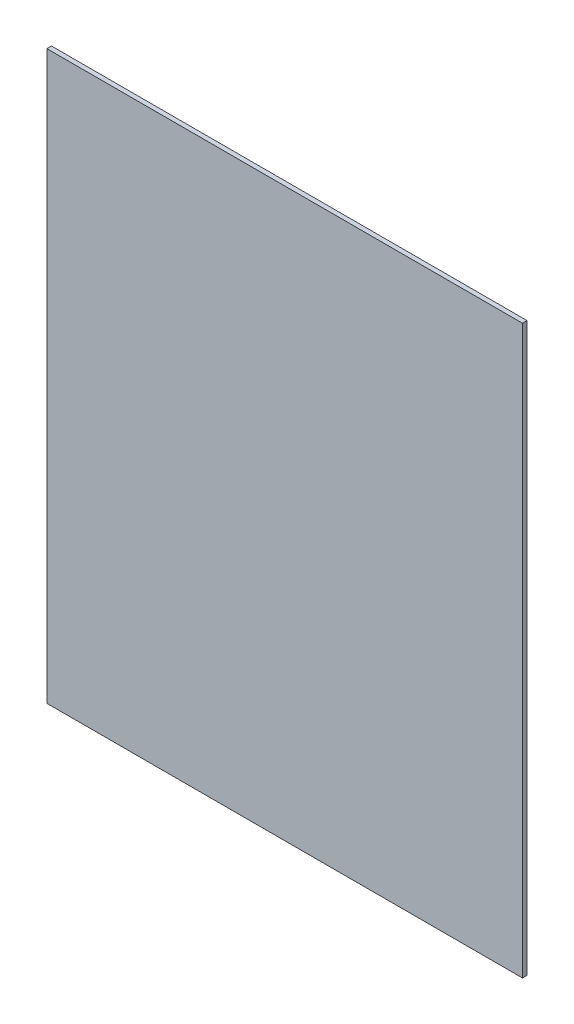
SolidWorks part; units mm, degrees
material "PC High Viscosity"
ref_plane "Front Plane" through (0, 0, 0) normal (0, 0, 1) x (1, 0, 0)
ref_plane "Top Plane" through (0, 0, 0) normal (0, 1, 0) x (1, 0, 0)
ref_plane "Right Plane" through (0, 0, 0) normal (1, 0, 0) x (0, 0, -1)
sketch "Sketch1" plane through (0, 0, 0) normal (0, 0, 1) x (1, 0, 0)
  line L1 (0, 0) -> (-165.1, 0)
  line L2 (0, 0) -> (0, 196.85)
  line L3 (0, 196.85) -> (-165.1, 196.85)
  line L4 (-165.1, 0) -> (-165.1, 196.85)
  dimension "D1" = 165.1
  dimension "D2" = 196.85
extrude "Boss-Extrude1" add sketch "Sketch1" along normal blind 1.5875
